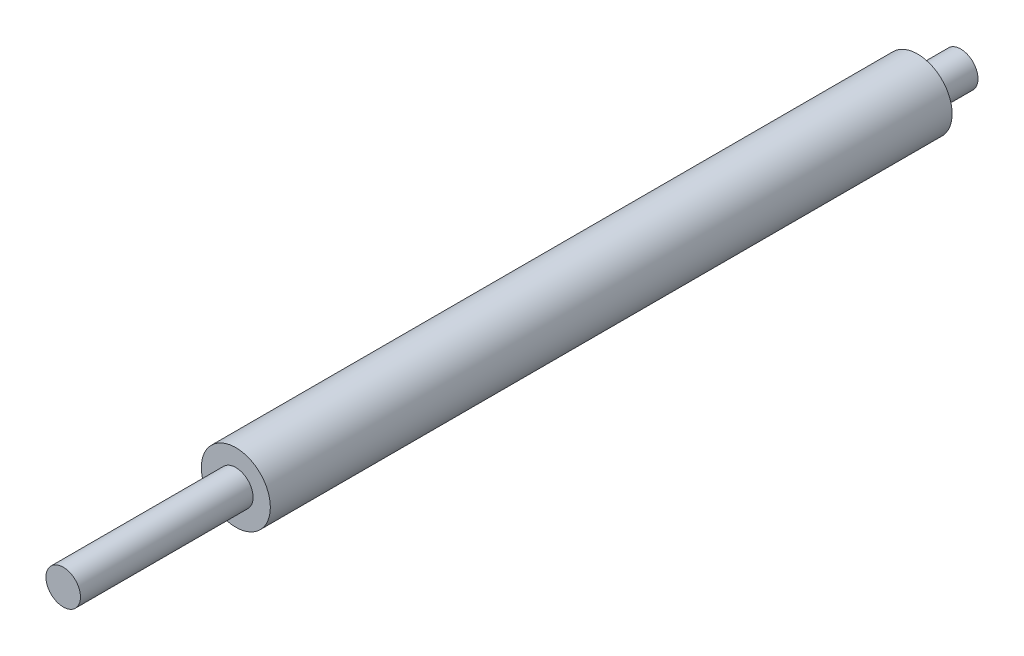
SolidWorks part; units mm, degrees
ref_plane "Front Plane" through (0, 0, 0) normal (0, 0, 1) x (1, 0, 0)
ref_plane "Top Plane" through (0, 0, 0) normal (0, 1, 0) x (1, 0, 0)
ref_plane "Right Plane" through (0, 0, 0) normal (1, 0, 0) x (0, 0, -1)
sketch "Sketch1" plane through (0, 0, 0) normal (0, 0, 1) x (1, 0, 0)
  circle A0 centre (0, 0) radius 6
  dimension "D1" = 12
extrude "Boss-Extrude1" add sketch "Sketch1" along normal mid plane 118.5
sketch "Sketch2" plane through (0, 0, 59.25) normal (0, 0, 1) x (1, 0, 0)
  circle A0 centre (0, 0) radius 3
  dimension "D1" = 6
sketch "Sketch3" plane through (0, 0, -59.25) normal (0, 0, -1) x (-1, 0, 0)
  circle A0 centre (0, 0) radius 3
  dimension "D1" = 6
extrude "Boss-Extrude3" add sketch "Sketch3" along normal blind 7.5
extrude "Boss-Extrude4" add sketch "Sketch2" along normal blind 30
